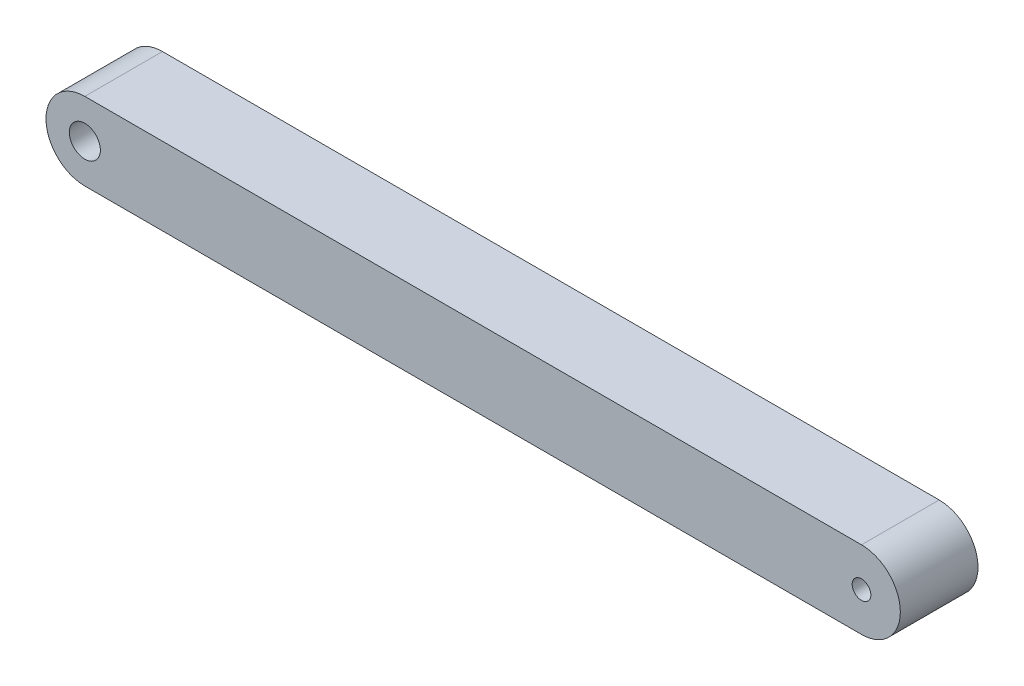
SolidWorks part; units mm, degrees
material "灰铸铁 (SN)"
ref_plane "前视基准面" through (0, 0, 0) normal (0, 0, 1) x (1, 0, 0)
ref_plane "上视基准面" through (0, 0, 0) normal (0, 1, 0) x (1, 0, 0)
ref_plane "右视基准面" through (0, 0, 0) normal (1, 0, 0) x (0, 0, -1)
sketch "草图1" plane through (0, 0, 0) normal (0, 0, 1) x (1, 0, 0)
  line L0 (-77.3942, 0) -> (22.6058, 0) construction
  line L1 (-77.3942, 5) -> (22.6058, 5)
  line L2 (-77.3942, -5) -> (22.6058, -5)
  arc A0 (-77.3942, 5) -> (-77.3942, -5) centre (-77.3942, 0) ccw
  arc A1 (22.6058, -5) -> (22.6058, 5) centre (22.6058, 0) ccw
  point P3 (-27.3942, 0)
  dimension "D2" = 5
  dimension "D1" = 100
extrude "凸台-拉伸1" add sketch "草图1" along normal blind 10
sketch "草图2" plane through (0, 0, 10) normal (0, 0, 1) x (1, 0, 0)
  circle A0 centre (-77.3942, 0) radius 2
  dimension "D1" = 4
extrude "切除-拉伸1" cut sketch "草图2" against normal through all
sketch "草图3" plane through (0, 0, 10) normal (0, 0, 1) x (1, 0, 0)
  circle A0 centre (22.6058, 0) radius 1.2
  dimension "D1" = 2.4
extrude "切除-拉伸2" cut sketch "草图3" against normal through all
